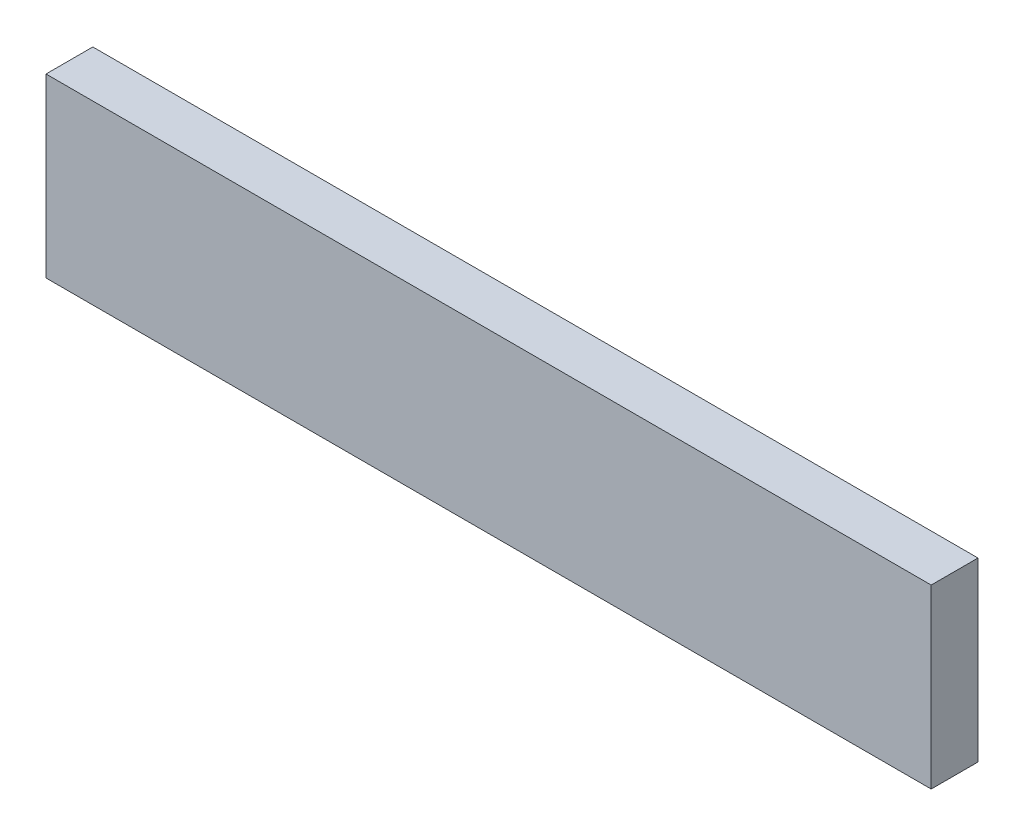
SolidWorks part; units mm, degrees
ref_plane "Front Plane" through (0, 0, 0) normal (0, 0, 1) x (1, 0, 0)
ref_plane "Top Plane" through (0, 0, 0) normal (0, 1, 0) x (1, 0, 0)
ref_plane "Right Plane" through (0, 0, 0) normal (1, 0, 0) x (0, 0, -1)
sketch "Sketch1" plane through (0, 0, 0) normal (1, 0, 0) x (0, 0, -1)
  line L0 (-0.1325, 0.5) -> (0.1325, -0.5) construction
  line L1 (0.1325, -0.5) -> (-0.1325, -0.5)
  line L2 (0.1325, -0.5) -> (0.1325, 0.5)
  line L3 (0.1325, 0.5) -> (-0.1325, 0.5)
  line L4 (-0.1325, -0.5) -> (-0.1325, 0.5)
  line L5 (0.1325, 0.5) -> (-0.1325, -0.5) construction
  point P9 (0, 0)
  dimension "DetectionLine_Y" = 1
  dimension "DetectionLine_Z" = 0.265
extrude "Boss-Extrude1" add sketch "Sketch1" along normal mid plane 5.01
